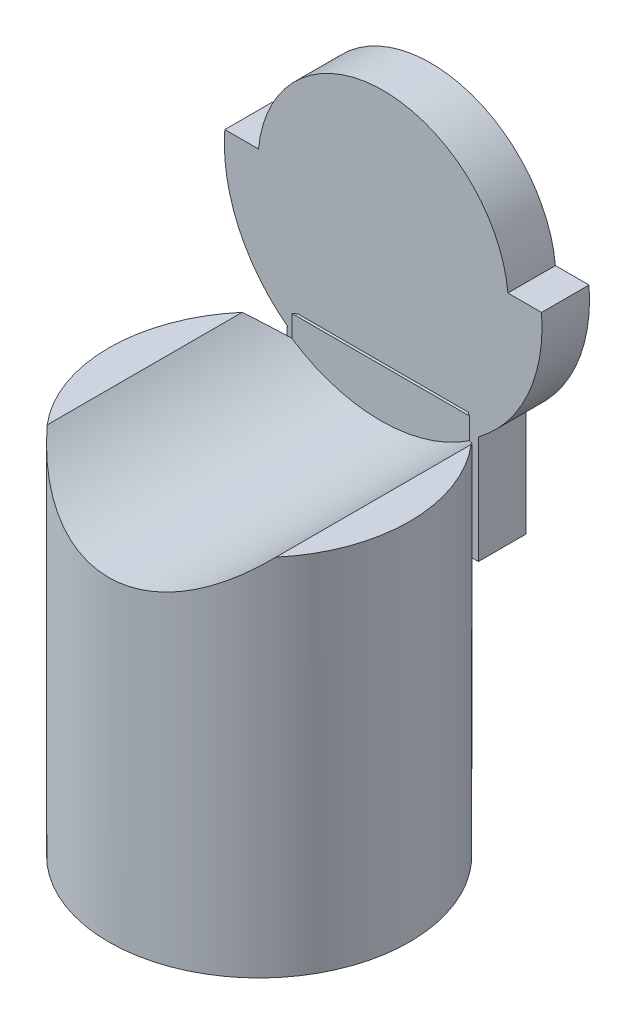
SolidWorks part; units mm, degrees
ref_plane "Front Plane" through (0, 0, 0) normal (0, 0, 1) x (1, 0, 0)
ref_plane "Top Plane" through (0, 0, 0) normal (0, 1, 0) x (1, 0, 0)
ref_plane "Right Plane" through (0, 0, 0) normal (1, 0, 0) x (0, 0, -1)
sketch "Sketch1" plane through (0, 0, 0) normal (0, 1, 0) x (1, 0, 0)
  circle A0 centre (0, 0) radius 0.0285
extrude "Boss-Extrude1" add sketch "Sketch1" against normal blind 0.069 from offset 0.021 offset against normal yes
sketch "Sketch2" plane through (0, 0, 0) normal (0, 0, 1) x (1, 0, 0)
  line L0 (-0.03, 0.0023) -> (-0.0236, 0.0023)
  line L1 (0.0236, 0.0023) -> (0.03, 0.0023)
  line L3 (-0.018, -0.0241) -> (-0.0182, -0.0241)
  line L4 (0.018, -0.0241) -> (0.018, -0.0446)
  line L5 (0.018, -0.0446) -> (-0.0182, -0.0446)
  line L6 (-0.0182, -0.0241) -> (-0.0182, -0.0446)
  arc A0 (0.0236, 0.0023) -> (-0.0236, 0.0023) centre (0, 0) ccw
  arc A1 (-0.03, 0.0023) -> (-0.018, -0.0241) centre (0, 0) ccw
  arc A2 (0.018, -0.0241) -> (0.03, 0.0023) centre (0, 0) ccw
extrude "Boss-Extrude2" add sketch "Sketch2" against normal blind 0.009 from offset 0.0235 offset against normal yes
sketch "Sketch3" plane through (0, 0, 0) normal (0, 0, 1) x (1, 0, 0)
  circle A0 centre (0, 0) radius 0.0302
extrude "Cut-Extrude1" cut sketch "Sketch3" against normal blind 0.023 and the other way through all
